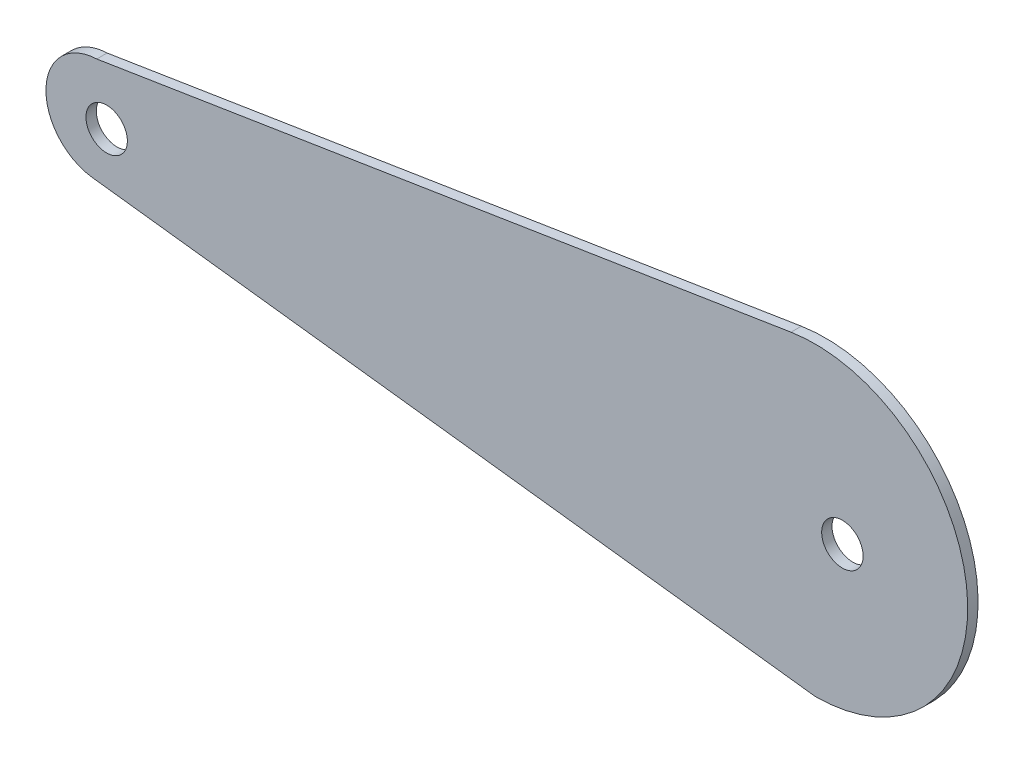
SolidWorks part; units mm, degrees
ref_plane "Front Plane" through (0, 0, 0) normal (0, 0, 1) x (1, 0, 0)
ref_plane "Top Plane" through (0, 0, 0) normal (0, 1, 0) x (1, 0, 0)
ref_plane "Right Plane" through (0, 0, 0) normal (1, 0, 0) x (0, 0, -1)
sketch "Sketch1" plane through (0, 0, 0) normal (0, 0, 1) x (1, 0, 0)
  line L0 (-69.3161, 3.879) -> (-2.3165, 14.5476)
  line L1 (-0.001, -14.7309) -> (-69.7535, -6.2408)
  arc A0 (-2.3165, 14.5476) -> (-0.001, -14.7309) centre (0, 0) cw
  arc A1 (-69.7535, -6.2408) -> (-69.3161, 3.879) centre (-69.1397, -1.198) cw
  point P5 (-74.2149, -0.9786)
  point P7 (14.6851, 1.1614)
  dimension "D2" = 5.08
  dimension "D1" = 88.9
  dimension "D4" = 14.6851
  dimension "D5" = 2.3165
extrude "Boss-Extrude1" add sketch "Sketch1" along normal blind 1
sketch "Sketch2" plane through (0, 0, 0) normal (0, 0, -1) x (-1, 0, 0)
  circle A0 centre (-2.6365, -0.6924) radius 2
  circle A1 centre (68.3619, -1.4982) radius 2
  dimension "D1" = 4
  dimension "D2" = 4
  dimension "D3" = 1.3916
  dimension "D4" = 72.39
  dimension "D5" = 16.0458
  dimension "D6" = 15.24
extrude "Cut-Extrude1" cut sketch "Sketch2" against normal blind 2.54
scale "Scale1" scale about centroid uniform scaling yes scale factor 1.3
